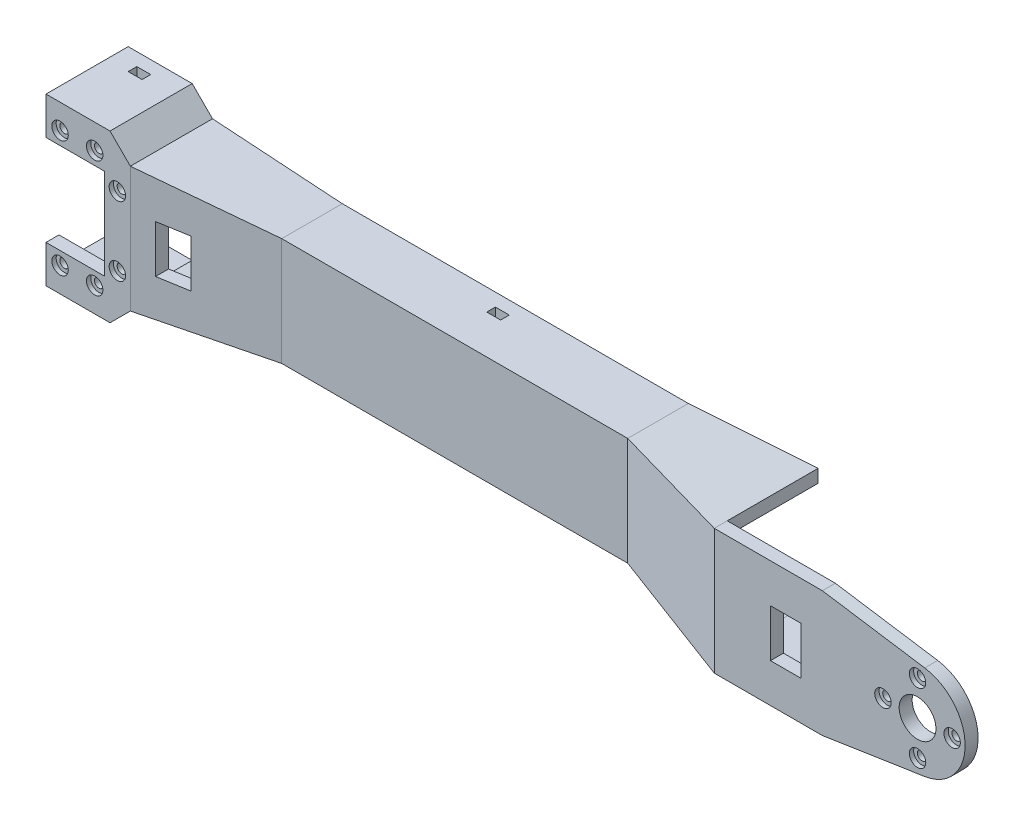
SolidWorks part; units mm, degrees
ref_plane "Front Plane" through (0, 0, 0) normal (0, 0, 1) x (1, 0, 0)
ref_plane "Top Plane" through (0, 0, 0) normal (0, 1, 0) x (1, 0, 0)
ref_plane "Right Plane" through (0, 0, 0) normal (1, 0, 0) x (0, 0, -1)
sketch "Sketch1" plane through (0, 0, 0) normal (0, 0, 1) x (1, 0, 0)
  line L0 (25, 29) -> (48.6663, 25.3731)
  line L1 (0, 0) -> (25, 0)
  line L2 (0, 0) -> (0, 29)
  line L3 (0, 29) -> (25, 29)
  line L5 (25, 0) -> (48.6663, 3.6269)
  line L6 (0, 14.5) -> (81.3972, 14.5) construction
  arc A0 (48.6663, 3.6269) -> (48.6663, 25.3731) centre (47, 14.5) ccw
  dimension "D1" = 22
  dimension "D2" = 29
  dimension "D3" = 22
  dimension "D4" = 25
extrude "Boss-Extrude1" add sketch "Sketch1" against normal blind 3
sketch "Sketch2" plane through (0, 0, 0) normal (0, 0, 1) x (1, 0, 0)
  line L0 (47, 22.5) -> (47, 6.5) construction
  line L1 (39, 14.5) -> (55, 14.5) construction
  circle A0 centre (47, 14.5) radius 4.25
  circle A1 centre (47, 22.5) radius 1.05
  circle A2 centre (55, 14.5) radius 1.05
  circle A3 centre (47, 6.5) radius 1.05
  circle A4 centre (39, 14.5) radius 1.05
  dimension "D1" = 8.5
  dimension "D3" = 2.1
  dimension "D2" = 16
extrude "Cut-Extrude1" cut sketch "Sketch2" against normal up to next
sketch "Sketch3" plane through (0, 0, 0) normal (0, 0, 1) x (1, 0, 0)
  circle A0 centre (47, 22.5) radius 1.9
  circle A1 centre (55, 14.5) radius 1.9
  circle A2 centre (47, 6.5) radius 1.9
  circle A3 centre (39, 14.5) radius 1.9
  dimension "D1" = 3.8
extrude "Cut-Extrude2" cut sketch "Sketch3" against normal blind 1
sketch "Sketch4" plane through (0, 29, 0) normal (0, 1, 0) x (1, 0, 0)
  line L0 (0, 3) -> (0, 0)
  line L1 (0, 0) -> (-30, 10)
  line L2 (-30, 10) -> (-110, 10)
  line L3 (-110, 10) -> (-140, 5)
  line L4 (-140, 5) -> (-140, 8)
  line L5 (-140, 8) -> (-110, 13)
  line L6 (-110, 13) -> (-30, 13)
  line L7 (-30, 13) -> (0, 3)
  line L8 (25, 0) -> (0, 0) construction
  dimension "D1" = 5
  dimension "D2" = 10
  dimension "D3" = 3
  dimension "D4" = 30
  dimension "D5" = 30
  dimension "D6" = 140
extrude "Boss-Extrude2" add sketch "Sketch4" against normal up to surface (29 mm away) up to face at (12.5, 0, -1.5)
ref_plane "Plane1" through (0, 0, -5) normal (0, 0, 1) x (1, 0, 0)
sketch "Sketch7" plane through (0, 0, -5) normal (0, 0, 1) x (1, 0, 0)
  line L0 (-140, 29) -> (-144.7, 33.7)
  line L1 (-140, 0) -> (-140, 29) construction
  line L2 (-144.7, 33.7) -> (-159.5, 33.7)
  line L3 (-159.5, 33.7) -> (-159.5, 25)
  line L4 (-159.5, 25) -> (-146, 25)
  line L5 (-146, 25) -> (-146, 4)
  line L6 (-146, 4) -> (-159.5, 4)
  line L7 (-159.5, 4) -> (-159.5, -4.7)
  line L8 (-159.5, -4.7) -> (-144.7, -4.7)
  line L9 (-144.7, -4.7) -> (-140, 0)
  line L10 (-140, 0) -> (-140, 29)
  line L11 (-146, 14.5) -> (-140, 14.5) construction
  point P4 (-140, 14.5)
  dimension "D1" = 8.7
  dimension "D2" = 6
  dimension "D3" = 13.5
  dimension "D4" = 45
  dimension "D6" = 38.4
extrude "Boss-Extrude4" add sketch "Sketch7" against normal blind 3
sketch "Sketch8" plane through (0, 0, -5) normal (0, 0, 1) x (1, 0, 0)
  line L0 (-156.25, 28) -> (-148.25, 28) construction
  line L1 (-148.25, 28) -> (-143, 22.5) construction
  line L2 (-143, 22.5) -> (-143, 6.5) construction
  line L3 (-143, 6.5) -> (-148.25, 1) construction
  line L4 (-148.25, 1) -> (-156.25, 1) construction
  line L6 (-146, 14.5) -> (-143, 14.5) construction
  line L7 (-146, 25) -> (-146, 4) construction
  circle A0 centre (-156.25, 28) radius 1.05
  circle A1 centre (-148.25, 28) radius 1.05
  circle A2 centre (-143, 22.5) radius 1.05
  circle A3 centre (-143, 6.5) radius 1.05
  circle A4 centre (-148.25, 1) radius 1.05
  circle A5 centre (-156.25, 1) radius 1.05
  dimension "D7" = 2.1
  dimension "D1" = 3
  dimension "D2" = 5.25
  dimension "D3" = 5.5
  dimension "D4" = 16
  dimension "D5" = 8
  dimension "D6" = 5.5
extrude "Cut-Extrude3" cut sketch "Sketch8" against normal up to next
sketch "Sketch9" plane through (0, 0, -5) normal (0, 0, 1) x (1, 0, 0)
  circle A0 centre (-156.25, 28) radius 1.9
  circle A1 centre (-148.25, 28) radius 1.9
  circle A2 centre (-143, 22.5) radius 1.9
  circle A3 centre (-143, 6.5) radius 1.9
  circle A4 centre (-148.25, 1) radius 1.9
  circle A5 centre (-156.25, 1) radius 1.9
  dimension "D1" = 3.8
extrude "Cut-Extrude4" cut sketch "Sketch9" against normal blind 1
sketch "Sketch11" plane through (0, 0, 0) normal (0, 0, 1) x (1, 0, 0)
  line L0 (0, 0) -> (-30, 2)
  line L1 (-30, 0) -> (-30, 29) construction
  line L2 (-30, 2) -> (-110, 2)
  line L3 (-110, 0) -> (-110, 29) construction
  line L4 (-110, 2) -> (-140, 0)
  line L5 (-140, 0) -> (-140, 29) construction
  line L6 (-140, 0) -> (0, 0)
  line L7 (0, 29) -> (-30, 27)
  line L8 (-30, 27) -> (-110, 27)
  line L9 (-110, 27) -> (-140, 29)
  line L10 (-140, 29) -> (0, 29)
  dimension "D1" = 25
extrude "Cut-Extrude5" cut sketch "Sketch11" against normal up to surface (13 mm away) up to face at (-70, 14.5, -13)
ref_plane "Plane2" through (0, 0, -24) normal (0, 0, 1) x (1, 0, 0)
sketch "Sketch14" plane through (0, 0, -24) normal (0, 0, 1) x (1, 0, 0)
  line L0 (-159.5, 33.7) -> (-159.5, 30.7)
  line L1 (-159.5, 33.7) -> (-159.5, 25) construction
  line L2 (-159.5, 30.7) -> (-144.7, 30.7)
  line L3 (-144.7, 30.7) -> (-140, 26)
  line L4 (-140, 0) -> (-140, 29) construction
  line L5 (-140, 26) -> (-110, 24)
  line L6 (-110, 2) -> (-110, 27) construction
  line L7 (-110, 24) -> (-30, 24)
  line L8 (-30, 2) -> (-30, 27) construction
  line L9 (-30, 24) -> (0, 26)
  line L10 (0, 29) -> (0, 0) construction
  line L11 (0, 26) -> (25, 26)
  line L12 (25, 26) -> (25, 29)
  line L13 (25, 29) -> (0, 29) construction
  line L14 (25, 29) -> (0, 29)
  line L15 (0, 29) -> (-30, 27)
  line L16 (-30, 27) -> (-110, 27)
  line L17 (-110, 27) -> (-140, 29)
  line L18 (-140, 29) -> (-144.7, 33.7)
  line L19 (-144.7, 33.7) -> (-159.5, 33.7)
  dimension "D1" = 3
  dimension "D2" = 3
  dimension "D3" = 25
extrude "Boss-Extrude8" add sketch "Sketch14" along normal up to body separate body
ref_plane "Plane3" through (0, 14.5, 0) normal (0, 1, 0) x (1, 0, 0)
mirror "Mirror1" about plane through (0, 14.5, 0) normal (0, 1, 0) of "Boss-Extrude8"
sketch "Sketch16" plane through (0, 33.7, 0) normal (0, 1, 0) x (1, 0, 0)
  line L0 (-27.1688, 24) -> (27.1688, 24) construction
  line L1 (-154.5, 21) -> (-151.3, 21)
  line L2 (-154.5, 21) -> (-154.5, 19)
  line L3 (-154.5, 19) -> (-151.3, 19)
  line L4 (-151.3, 21) -> (-151.3, 19)
  line L5 (-159.5, 24) -> (-159.5, 5) construction
  line L6 (-30, 24) -> (-110, 24) construction
  line L7 (-71.6, 21) -> (-68.4, 21)
  line L8 (-71.6, 21) -> (-71.6, 19)
  line L9 (-71.6, 19) -> (-68.4, 19)
  line L10 (-68.4, 21) -> (-68.4, 19)
  line L12 (-70, 10) -> (-70, 24) construction
  line L13 (9, 19) -> (12.2, 19)
  line L14 (9, 19) -> (9, 21)
  line L15 (9, 21) -> (12.2, 21)
  line L16 (12.2, 19) -> (12.2, 21)
  line L17 (0, 24) -> (0, 0) construction
  line L18 (-110, 10) -> (-30, 10) construction
  point P24 (-70, 19)
  dimension "D1" = 3.2
  dimension "D2" = 2
  dimension "D3" = 3
  dimension "D4" = 5
  dimension "D5" = 3.2
  dimension "D6" = 2
  dimension "D7" = 3
  dimension "D9" = 3.2
  dimension "D10" = 2
  dimension "D11" = 3
  dimension "D12" = 9
extrude "Cut-Extrude6" cut sketch "Sketch16" against normal through all
sketch "Sketch17" plane through (0, 0, 0) normal (0, 0, 1) x (1, 0, 0)
  line L0 (47, 14.5) -> (-100.5533, 14.5) construction
  line L1 (-140, 0) -> (-140, 29) construction
  line L2 (-135, 9) -> (-128, 9)
  line L3 (-135, 9) -> (-135, 20)
  line L4 (-135, 20) -> (-128, 20)
  line L5 (-128, 9) -> (-128, 20)
  line L6 (-135, 9) -> (-128, 20) construction
  line L7 (-135, 20) -> (-128, 9) construction
  line L8 (13, 9) -> (20, 9)
  line L9 (13, 9) -> (13, 20)
  line L10 (13, 20) -> (20, 20)
  line L11 (20, 9) -> (20, 20)
  line L12 (13, 9) -> (20, 20) construction
  line L13 (13, 20) -> (20, 9) construction
  point P3 (-131.5, 14.5)
  point P8 (16.5, 14.5)
  dimension "D1" = 7
  dimension "D2" = 11
  dimension "D3" = 5
  dimension "D4" = 5
extrude "Cut-Extrude7" cut sketch "Sketch17" against normal up to next
sketch "Sketch18" plane through (0, 0, -24) normal (0, 0, -1) x (-1, 0, 0)
  line L1 (-25, 29) -> (0, 29)
  line L2 (-25, 29) -> (-25, 26)
  line L3 (-25, 26) -> (0, 26)
  line L4 (0, 29) -> (0, 26)
extrude "Cut-Extrude8" cut sketch "Sketch18" against normal up to surface (21 mm away) up to face at (16.5, 14.5, -3)
